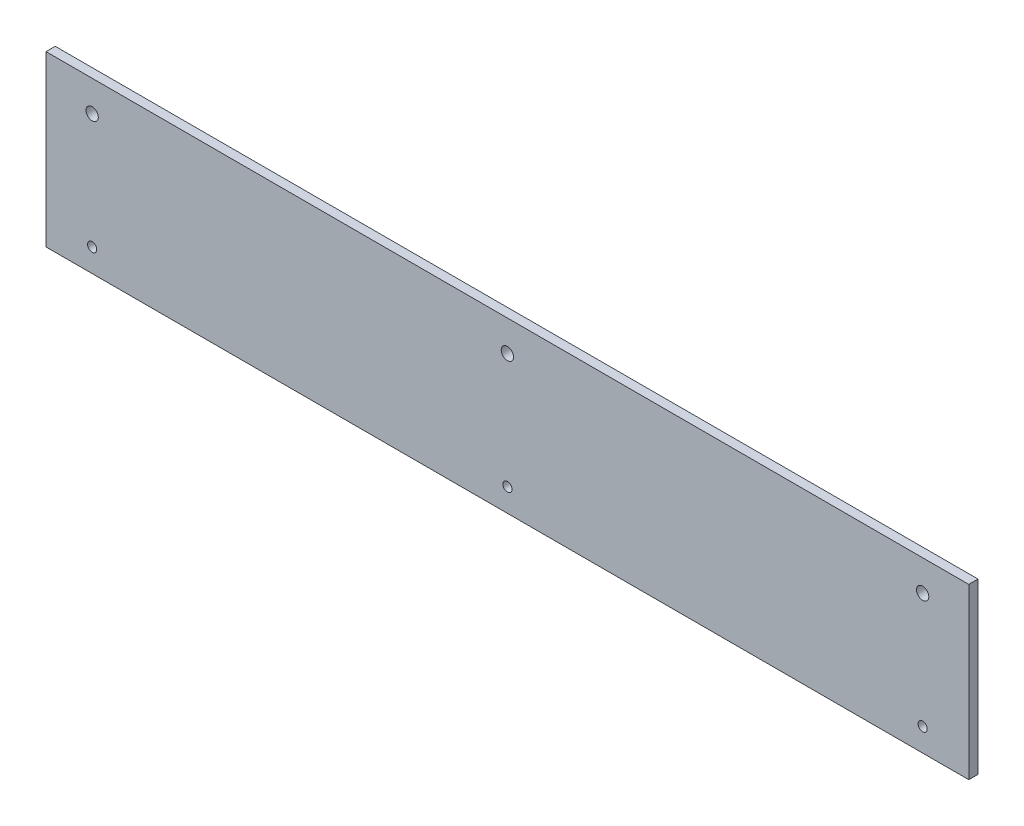
SolidWorks part; units mm, degrees
ref_plane "Front Plane" through (0, 0, 0) normal (0, 0, 1) x (1, 0, 0)
ref_plane "Top Plane" through (0, 0, 0) normal (0, 1, 0) x (1, 0, 0)
ref_plane "Right Plane" through (0, 0, 0) normal (1, 0, 0) x (0, 0, -1)
sketch "Sketch1" plane through (0, 0, 0) normal (0, 0, 1) x (1, 0, 0)
  line L0 (0, 15) -> (300, 15)
  line L1 (0, 0) -> (300, 0)
  line L2 (0, 0) -> (0, 55)
  line L3 (0, 55) -> (300, 55)
  line L4 (300, 0) -> (300, 55)
  circle A0 centre (15, 45) radius 2
  circle A1 centre (150, 45) radius 2
  circle A2 centre (285, 45) radius 2
  circle A3 centre (15, 7.5) radius 1.5
  circle A4 centre (150, 7.5) radius 1.5
  circle A5 centre (285, 7.5) radius 1.5
  point P19 (0, 0)
  point P20 (0, 0)
  point P21 (0, 0)
  point P22 (0, 0)
  point P23 (0, 0)
  point P24 (0, 0)
  point P25 (0, 0)
  dimension "D6" = 4
  dimension "D7" = 15
  dimension "D10" = 3
  dimension "D1" = 300
  dimension "D2" = 55
  dimension "D3" = 15
  dimension "D4" = 135
  dimension "D5" = 135
  dimension "D8" = 10
  dimension "D9" = 7.5
extrude "Boss-Extrude1" add sketch "Sketch1" along normal blind 3 contours L0 L4 L3 L2 A2 A1 A0 | L1 L4 L0 L2
